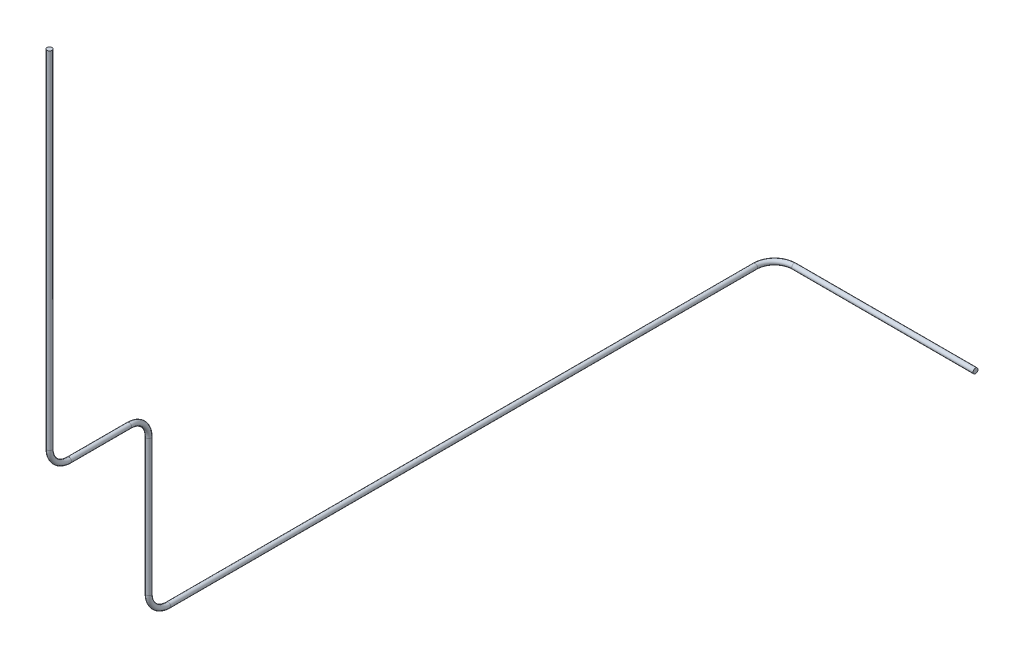
SolidWorks part; units mm, degrees
ref_plane "Alzado" through (0, 0, 0) normal (0, 0, 1) x (1, 0, 0)
ref_plane "Planta" through (0, 0, 0) normal (0, 1, 0) x (1, 0, 0)
ref_plane "Vista lateral" through (0, 0, 0) normal (1, 0, 0) x (0, 0, -1)
sketch3d "Croquis3D2"
  line L0 (-1396.5372, -951.2627, 1871.1198) -> (-1396.5372, -956.7476, 1867.92) construction
  line L3 (-1396.5372, -956.7476, 1867.92) -> (-1859.8143, -956.7476, 1867.92)
  line L4 (-1909.8143, -956.7476, 1917.92) -> (-1909.8143, -956.7476, 3416.9793)
  line L5 (-1909.8143, -906.7476, 3466.9793) -> (-1909.8143, -559.2533, 3466.9793)
  line L6 (-1909.8143, -509.2533, 3516.9793) -> (-1909.8143, -509.2533, 3670.1905)
  line L7 (-1909.8143, -459.2533, 3720.1905) -> (-1909.8143, 425.1806, 3720.1905)
  arc A1 (-1909.8143, -509.2533, 3670.1905) -> (-1909.8143, -459.2533, 3720.1905) centre (-1909.8143, -459.2533, 3670.1905) ccw
  arc A2 (-1909.8143, -559.2533, 3466.9793) -> (-1909.8143, -509.2533, 3516.9793) centre (-1909.8143, -559.2533, 3516.9793) ccw
  arc A3 (-1909.8143, -956.7476, 3416.9793) -> (-1909.8143, -906.7476, 3466.9793) centre (-1909.8143, -906.7476, 3416.9793) ccw
  arc A4 (-1859.8143, -956.7476, 1867.92) -> (-1909.8143, -956.7476, 1917.92) centre (-1859.8143, -956.7476, 1917.92) ccw
  point P4 (-1909.8143, -509.2533, 3720.1905)
  point P6 (-1959.8143, -459.2533, 3670.1905)
  point P12 (-1909.8143, -509.2533, 3466.9793)
  point P21 (-1859.8143, -559.2533, 3516.9793)
  point P24 (-1909.8143, -956.7476, 3466.9793)
  point P25 (-1959.8143, -906.7476, 3416.9793)
  point P28 (-1909.8143, -956.7476, 1867.92)
  point P29 (-1859.8143, -906.7476, 1917.92)
  dimension "D1" = 50
  dimension "D2" = 513.2771
  dimension "D3" = 1599.0593
  dimension "D4" = 447.4944
  dimension "D5" = 253.2112
  dimension "D6" = 934.4338
sweep "Barrer2" add path "Croquis3D2" circular profile diameter 12.7 parameters "D3"=12.7
